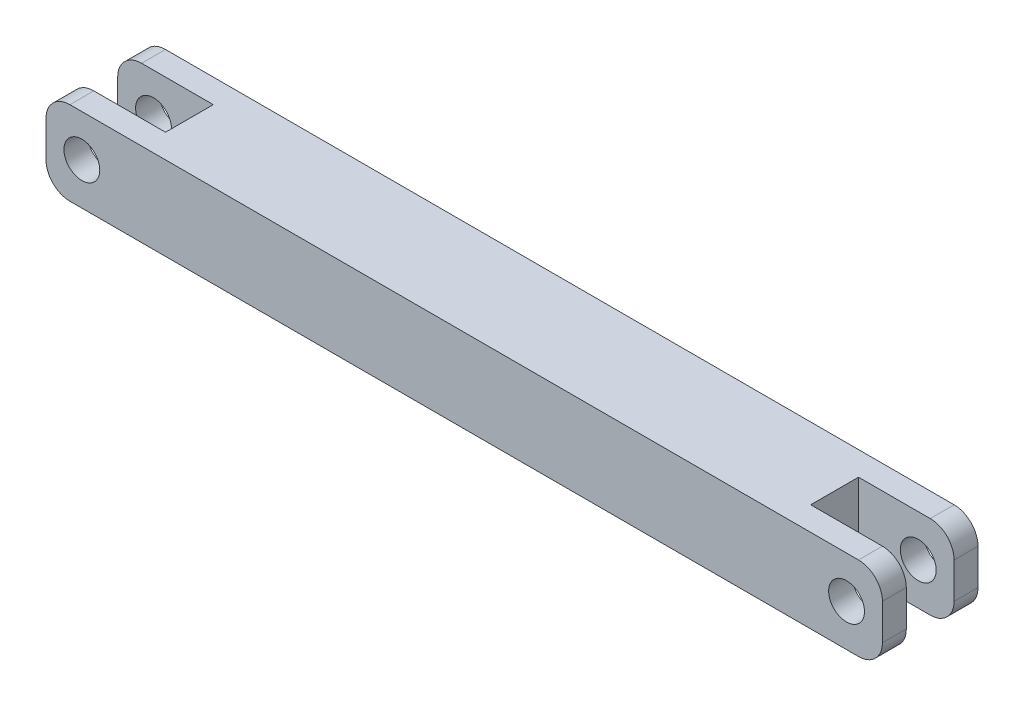
SolidWorks part; units mm, degrees
ref_plane "Front Plane" through (0, 0, 0) normal (0, 0, 1) x (1, 0, 0)
ref_plane "Top Plane" through (0, 0, 0) normal (0, 1, 0) x (1, 0, 0)
ref_plane "Right Plane" through (0, 0, 0) normal (1, 0, 0) x (0, 0, -1)
sketch "Sketch1" plane through (0, 0, 0) normal (0, 0, 1) x (1, 0, 0)
  line L1 (-175, 17.5) -> (175, 17.5)
  line L2 (-175, 17.5) -> (-175, -17.5)
  line L3 (-175, -17.5) -> (175, -17.5)
  line L4 (175, 17.5) -> (175, -17.5)
  line L5 (-175, 17.5) -> (175, -17.5) construction
  line L6 (-175, -17.5) -> (175, 17.5) construction
  point P0 (0, 0)
  dimension "D1" = 350
  dimension "D2" = 35
extrude "Boss-Extrude1" add sketch "Sketch1" along normal mid plane 40
sketch "Sketch2" plane through (0, 0, 0) normal (0, 1, 0) x (1, 0, 0)
  line L0 (-175, -20) -> (-175, 20) construction
  line L1 (-215, 10) -> (-135, 10)
  line L2 (-215, 10) -> (-215, -10)
  line L3 (-215, -10) -> (-135, -10)
  line L4 (-135, 10) -> (-135, -10)
  line L5 (-215, 10) -> (-135, -10) construction
  line L6 (-215, -10) -> (-135, 10) construction
  point P0 (-175, 0)
  dimension "D1" = 20
  dimension "D2" = 40
extrude "Cut-Extrude1" cut sketch "Sketch2" against normal through all both and the other way through all
sketch "Sketch4" plane through (0, 0, 0) normal (0, 0, 1) x (1, 0, 0)
  line L0 (-175, 17.5) -> (-175, -17.5) construction
  circle A0 centre (-160, 0) radius 7.5
  point P4 (0, 0)
  dimension "D1" = 15
  dimension "D2" = 15
extrude "Cut-Extrude2" cut sketch "Sketch4" against normal through all both and the other way through all
fillet "Fillet1" radius 10 4 edges at (-175, -17.5, -15) (-175, -17.5, 15) (-175, 17.5, -15) (-175, 17.5, 15)
mirror "Mirror3" about plane through (0, 0, 0) normal (1, 0, 0) of "Cut-Extrude2", "Cut-Extrude1"
fillet "Fillet2" radius 10 4 edges at (175, -17.5, 15) (175, -17.5, -15) (175, 17.5, -15) (175, 17.5, 15)
